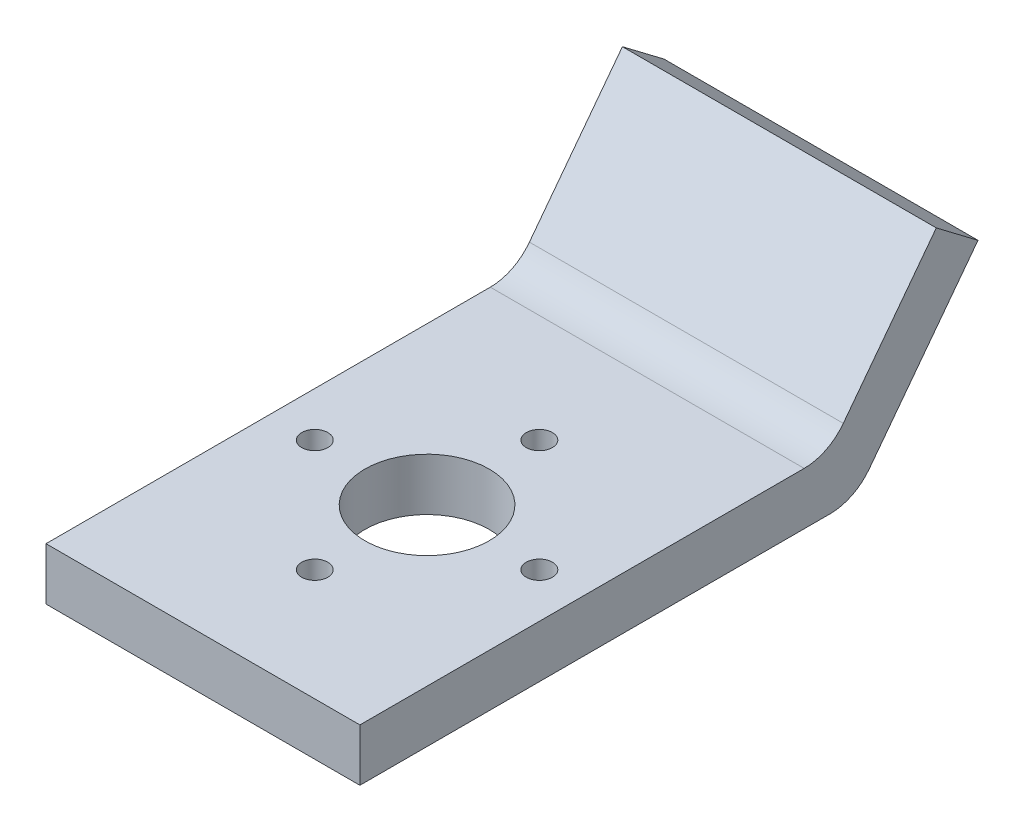
SolidWorks part; units mm, degrees
ref_plane "Front Plane" through (0, 0, 0) normal (0, 0, 1) x (1, 0, 0)
ref_plane "Top Plane" through (0, 0, 0) normal (0, 1, 0) x (1, 0, 0)
ref_plane "Right Plane" through (0, 0, 0) normal (1, 0, 0) x (0, 0, -1)
sketch "Sketch1" plane through (0, 0, 0) normal (1, 0, 0) x (0, 0, -1)
  line L1 (34.0237, 28.9395) -> (91.1075, 28.9395)
  line L2 (95.8559, 31.2997) -> (109.047, 48.7161)
  line L4 (34.0237, 35.2895) -> (87.9512, 35.2895)
  line L5 (92.6996, 37.6497) -> (103.985, 52.55)
  line L6 (31.8823, 35.2895) -> (90.912, 35.2895) construction
  line L7 (109.047, 48.7161) -> (103.985, 52.55)
  line L9 (0, 0) -> (34.208, 28.9395) construction
  line L10 (-4.1013, 4.8479) -> (31.8823, 35.2895) construction
  line L11 (90.912, 35.2895) -> (103.985, 52.55) construction
  line L12 (34.208, 28.9395) -> (94.0683, 28.9395) construction
  line L13 (94.0683, 28.9395) -> (109.047, 48.7161) construction
  line L14 (34.0237, 35.2895) -> (34.0237, 28.9395)
  arc A1 (87.9512, 35.2895) -> (92.6996, 37.6497) centre (87.9512, 41.2461) ccw
  arc A3 (91.1075, 28.9395) -> (95.8559, 31.2997) centre (91.1075, 34.8961) ccw
  dimension "D1" = 6.35
extrude "Extrude1" add sketch "Sketch1" against normal blind 38.1
sketch "Sketch2" plane through (0, 0, 0) normal (0, 1, 0) x (1, 0, 0)
  line L0 (0, 31.538) -> (-38.1, 90.912) construction
  line L2 (-38.1, 90.912) -> (0, 90.912) construction
  circle A0 centre (-19.05, 61.225) radius 7.5436
  circle A2 centre (-32.6777, 61.225) radius 1.5869
  circle A3 centre (-19.05, 74.8527) radius 1.5869
  circle A4 centre (-5.4223, 61.225) radius 1.5869
  circle A5 centre (-19.05, 47.5974) radius 1.5869
extrude "Extrude2" cut sketch "Sketch2" along normal blind 38.1
